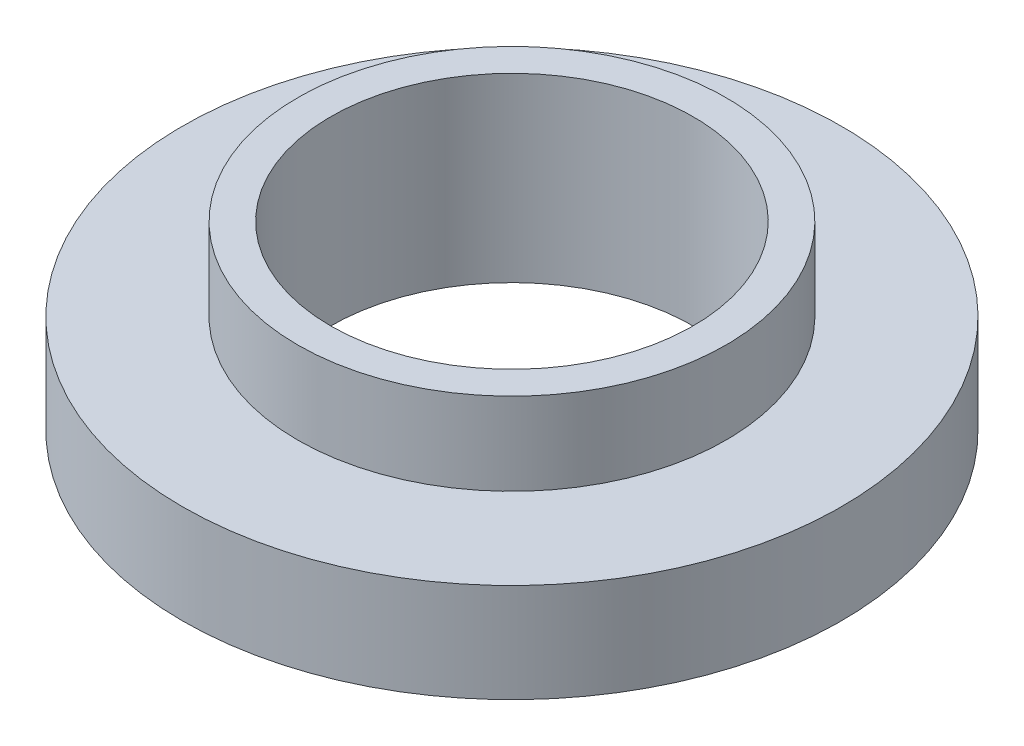
SolidWorks part; units mm, degrees
ref_plane "前视基准面" through (0, 0, 0) normal (0, 0, 1) x (1, 0, 0)
ref_plane "上视基准面" through (0, 0, 0) normal (0, 1, 0) x (1, 0, 0)
ref_plane "右视基准面" through (0, 0, 0) normal (1, 0, 0) x (0, 0, -1)
sketch "草图1" plane through (0, 0, 0) normal (0, 1, 0) x (1, 0, 0)
  circle A0 centre (0, 0) radius 20
  circle A1 centre (0, 0) radius 11
  dimension "D1" = 22
  dimension "D2" = 40
extrude "凸台-拉伸1" add sketch "草图1" along normal blind 6
sketch "草图2" plane through (0, 6, 0) normal (0, 1, 0) x (1, 0, 0)
  circle A0 centre (0, 0) radius 11
  circle A1 centre (0, 0) radius 13
  dimension "D1" = 2
  dimension "D2" = 22
extrude "凸台-拉伸2" add sketch "草图2" along normal blind 5
hole_wizard "M3 螺纹孔1" positions "草图3" profile "草图4" tap size "M3" standard "GB"
sketch "草图3" plane through (0, 0, 0) normal (0, -1, 0) x (-1, 0, 0)
  circle A0 centre (0, 0) radius 14 construction
  point P0 (-14, 0)
  point P2 (0, -14)
  point P4 (14, 0)
  point P6 (0, 14)
  point P13 (0, -14)
  point P14 (0, 14)
  point P15 (14, 0)
  point P16 (-14, 0)
  dimension "D1" = 28
sketch "草图4" plane through (14, 0, 0) normal (1, 0, 0) x (0, 0, -1)
  line L0 (0, 0) -> (0, 5.7511)
  line L1 (0, 5.7511) -> (1.25, 5)
  line L2 (1.25, 5) -> (1.25, 0)
  line L5 (1.25, 0) -> (0, 0)
  line L10 (0, 5.7511) -> (-1.25, 5) construction
  line L11 (0, -6.35) -> (0, 107.95) construction
  dimension "螺纹孔钻头直径" = 2.5
  dimension "螺纹孔钻头深度" = 5
  dimension "导头角度" = 118
cosmetic thread "孔螺蚊线1"
cosmetic thread "孔螺蚊线2"
cosmetic thread "孔螺蚊线3"
cosmetic thread "孔螺蚊线4"
